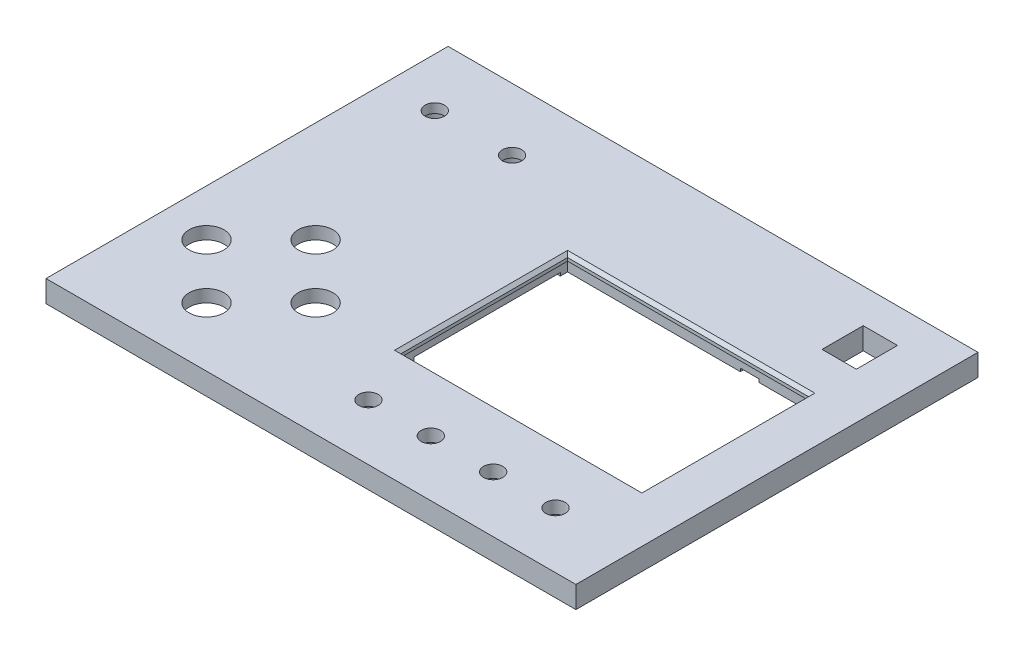
SolidWorks part; units mm, degrees
ref_plane "Front Plane" through (0, 0, 0) normal (0, 0, 1) x (1, 0, 0)
ref_plane "Top Plane" through (0, 0, 0) normal (0, 1, 0) x (1, 0, 0)
ref_plane "Right Plane" through (0, 0, 0) normal (1, 0, 0) x (0, 0, -1)
sketch "Sketch1" plane through (0, 0, 0) normal (0, 1, 0) x (1, 0, 0)
  line L1 (52.5, -34.5) -> (-52.5, -34.5)
  line L2 (52.5, -34.5) -> (52.5, 34.5)
  line L3 (52.5, 34.5) -> (-52.5, 34.5)
  line L4 (-52.5, -34.5) -> (-52.5, 34.5)
  line L5 (52.5, -34.5) -> (-52.5, 34.5) construction
  line L6 (52.5, 34.5) -> (-52.5, -34.5) construction
  point P0 (0, 0)
  dimension "D1" = 105
  dimension "D2" = 69
extrude "Boss-Extrude1" add sketch "Sketch1" along normal blind 5
extrude "Cut-Extrude1" cut sketch "Sketch2" against normal through all
sketch "Sketch2" plane through (17.0721, 0, 5.1034) normal (0, -1, 0) x (-1, 0, 0)
  line L0 (59.7281, 33.0909) -> (-27.1079, 33.0909)
  line L1 (-27.1079, 33.0909) -> (-27.1079, -24.4081)
  line L2 (-27.1079, -24.4081) -> (59.7281, -24.4081)
  line L3 (59.7281, -24.4081) -> (59.7281, 33.0909)
  line L8 (-26.1079, -23.4081) -> (58.7281, -23.4081) construction
  line L9 (-26.1079, 32.0909) -> (-26.1079, -23.4081) construction
  line L10 (58.7281, 32.0909) -> (-26.1079, 32.0909) construction
  line L11 (58.7281, -23.4081) -> (58.7281, 32.0909) construction
extrude "Cut-Extrude2" cut sketch "Sketch3" against normal blind 1
sketch "Sketch3" plane through (17.0721, 0, 5.1034) normal (0, -1, 0) x (-1, 0, 0)
  line L1 (59.8221, 30.7659) -> (54.5248, 30.7659)
  line L2 (59.8221, 30.7659) -> (59.8221, -16.2341) construction
  line L3 (59.8221, -16.2341) -> (54.5248, -16.2341)
  line L8 (65.3221, 30.2659) -> (60.3221, 30.2659) construction
  line L9 (60.3221, 30.2659) -> (60.3221, -15.7341) construction
  line L10 (60.3221, -15.7341) -> (65.3221, -15.7341) construction
  line L11 (65.3221, -15.7341) -> (65.3221, 30.2659) construction
  line L12 (54.5248, 30.7659) -> (54.5248, -16.2341)
  line L20 (65.8221, 30.7659) -> (59.8221, 30.7659)
  line L21 (59.8221, 30.7659) -> (59.8221, -16.2341) construction
  line L22 (59.8221, -16.2341) -> (65.8221, -16.2341)
  line L23 (65.8221, -16.2341) -> (65.8221, 30.7659)
extrude "Cut-Extrude3" cut sketch "Sketch4" against normal blind 1
sketch "Sketch4" plane through (17.0721, 0, 5.1034) normal (0, -1, 0) x (-1, 0, 0)
  line L8 (69.5721, -29.3966) -> (69.5721, 69.6034)
  line L10 (-35.4279, 69.6034) -> (-35.4279, -29.3966)
  line L11 (-35.4279, -29.3966) -> (69.5721, -29.3966)
  line L16 (3.8121, 35.2559) -> (-1.1879, 35.2559)
  line L17 (-1.1879, 35.2559) -> (-1.1879, 32.7559)
  line L18 (-1.1879, 32.7559) -> (3.8121, 32.7559)
  line L19 (3.8121, 32.7559) -> (3.8121, 35.2559)
  line L20 (69.5721, 69.6034) -> (-35.4279, 69.6034)
  line L28 (4.3121, 35.7559) -> (-1.6879, 35.7559)
  line L29 (-1.6879, 35.7559) -> (-1.6879, 32.2559)
  line L30 (-1.6879, 32.2559) -> (4.3121, 32.2559)
  line L31 (4.3121, 32.2559) -> (4.3121, 35.7559)
extrude "Cut-Extrude4" cut sketch "Sketch5" against normal through all contours L3 L2 A3 L5 A2 L4 | L2 L3 L4 A4 L6 A5
sketch "Sketch5" plane through (17.0721, 0, 5.1034) normal (0, -1, 0) x (-1, 0, 0)
  line L2 (-27.1779, 33.1034) -> (-27.1779, 13.8376)
  line L3 (-27.1779, 5.1034) -> (-31.6779, 5.1034) construction
  line L4 (-31.6779, -0.8966) -> (-31.6779, 11.1034)
  line L5 (-30.1159, 12.6653) -> (-28.3501, 12.6653)
  line L6 (-29.4785, -3.0961) -> (-28.6478, -3.0961)
  line L7 (-27.1779, 5.1034) -> (-27.1779, 13.8376) construction
  line L8 (-27.1779, -4.566) -> (-18.8659, -4.566)
  line L9 (-27.1779, -4.566) -> (-27.1779, 5.1034)
  line L10 (-27.1779, 13.8376) -> (-18.8659, 13.8376)
  line L11 (-18.8659, -4.566) -> (-18.8659, 13.8376)
  line L12 (-27.1779, 13.8376) -> (-27.1779, 5.1034) construction
  line L13 (-27.1779, 5.1034) -> (-27.1779, -22.8966)
  arc A2 (-31.6779, 11.1034) -> (-30.1159, 12.6653) centre (-30.1159, 11.1034) cw
  arc A3 (-28.3501, 12.6653) -> (-27.1779, 13.8376) centre (-28.3501, 13.8376) ccw
  arc A4 (-31.6779, -0.8966) -> (-29.4785, -3.0961) centre (-29.4785, -0.8966) ccw
  arc A5 (-28.6478, -3.0961) -> (-27.1779, -4.566) centre (-28.6478, -4.566) cw
  point P8 (-31.6779, 5.1034)
extrude "Cut-Extrude7" cut sketch "Sketch9" against normal blind 4
sketch "Sketch9" plane through (17.0721, 0, 5.1034) normal (0, -1, 0) x (-1, 0, 0)
  circle A4 centre (-28.6779, -22.8966) radius 1.5 construction
  circle A5 centre (62.8221, -22.8966) radius 1.5 construction
  circle A6 centre (62.8221, 33.1034) radius 1.5 construction
  circle A7 centre (-28.6779, 33.1034) radius 1.5 construction
  circle A8 centre (-28.6779, 33.1034) radius 1
  circle A9 centre (62.8221, 33.1034) radius 1
  circle A10 centre (-28.6779, -22.8966) radius 1
  circle A11 centre (62.8221, -22.8966) radius 1
sketch "Sketch7" plane through (0, 5, 0) normal (0, 1, 0) x (1, 0, 0)
  line L1 (52.5, 34.5) -> (-52.5, 34.5)
  line L2 (52.5, 34.5) -> (52.5, 64.5)
  line L3 (52.5, 64.5) -> (-52.5, 64.5)
  line L4 (-52.5, 34.5) -> (-52.5, 64.5)
  line L5 (-52.5, -34.5) -> (52.5, -34.5)
  line L6 (-52.5, -34.5) -> (-52.5, -64.5)
  line L7 (-52.5, -64.5) -> (52.5, -64.5)
  line L8 (52.5, -34.5) -> (52.5, -64.5)
  line M17 (-52.5, -34.5) -> (52.5, -34.5)
  dimension "D1" = 30
  dimension "D2" = 30
extrude "Boss-Extrude2" add sketch "Sketch7" against normal up to surface (5 mm away) contours L8 L5 L7 M17 | L1 L4 L3 L2 up to face at (-45.75, 0, -29)
sketch "Sketch8" plane through (0, 5, 0) normal (0, 1, 0) x (1, 0, 0)
  line L0 (52.5, 29.2726) -> (52.5, 64.5) construction
  line L1 (52.5, -64.5) -> (52.5, 64.5) construction
  line L2 (52.5, 46.8863) -> (26.68, 46.8863) construction
  line L3 (-52.5, 64.5) -> (-52.5, -64.5) construction
  line L4 (19.635, 46.8863) -> (19.635, 53.4863) construction
  line L5 (37.68, 40.2863) -> (26.68, 40.2863)
  line L6 (37.68, 40.2863) -> (37.68, 53.4863)
  line L7 (37.68, 53.4863) -> (26.68, 53.4863)
  line L8 (26.68, 40.2863) -> (26.68, 53.4863)
  line L9 (37.68, 40.2863) -> (26.68, 53.4863) construction
  line L10 (37.68, 53.4863) -> (26.68, 40.2863) construction
  line L11 (19.635, 40.2863) -> (8.635, 40.2863) construction
  line L12 (8.635, 40.2863) -> (8.635, 46.8863) construction
  line L13 (19.635, 53.4863) -> (8.635, 53.4863) construction
  line L14 (1.59, 46.8863) -> (1.59, 53.4863) construction
  line L15 (1.59, 40.2863) -> (-9.41, 40.2863) construction
  line L16 (-9.41, 46.8863) -> (-9.41, 53.4863) construction
  line L17 (1.59, 53.4863) -> (-9.41, 53.4863) construction
  line L18 (-16.455, 40.2863) -> (-16.455, 46.8863) construction
  line L19 (-16.455, 40.2863) -> (-27.455, 40.2863) construction
  line L20 (-27.455, 40.2863) -> (-27.455, 46.8863) construction
  line L21 (-16.455, 53.4863) -> (-27.455, 53.4863) construction
  line L22 (-34.5, 40.2863) -> (-34.5, 46.8863) construction
  line L23 (-34.5, 40.2863) -> (-45.5, 40.2863) construction
  line L24 (-45.5, 40.2863) -> (-45.5, 46.8863) construction
  line L25 (-34.5, 53.4863) -> (-45.5, 53.4863) construction
  line L26 (-45.5, 46.8863) -> (-45.5, 53.4863) construction
  line L27 (-34.5, 46.8863) -> (-34.5, 53.4863) construction
  line L28 (-27.455, 46.8863) -> (-34.5, 46.8863) construction
  line L29 (-34.5, 46.8863) -> (-52.5, 46.8863) construction
  line L30 (-16.455, 46.8863) -> (-27.455, 46.8863) construction
  line L31 (-27.455, 46.8863) -> (-27.455, 53.4863) construction
  line L32 (-16.455, 46.8863) -> (-16.455, 53.4863) construction
  line L33 (1.59, 40.2863) -> (1.59, 46.8863) construction
  line L34 (-9.41, 40.2863) -> (-9.41, 46.8863) construction
  line L35 (-9.41, 46.8863) -> (-16.455, 46.8863) construction
  line L36 (8.635, 46.8863) -> (8.635, 53.4863) construction
  line L37 (8.635, 46.8863) -> (1.59, 46.8863) construction
  line L38 (1.59, 46.8863) -> (-9.41, 46.8863) construction
  line L39 (19.635, 40.2863) -> (19.635, 46.8863) construction
  line L40 (26.68, 46.8863) -> (19.635, 46.8863) construction
  line L41 (19.635, 46.8863) -> (8.635, 46.8863) construction
  point P9 (32.18, 46.8863)
  point P14 (-40, 53.4863)
  dimension "D1" = 13.2
  dimension "D2" = 11
  dimension "D3" = 20.32
  dimension "D5" = 12.5
  dimension "D6" = 11
  dimension "D4" = 5
extrude "Cut-Extrude6" cut sketch "Sketch8" against normal through all
sketch "Sketch10" plane through (0, 5, 0) normal (0, 1, 0) x (1, 0, 0)
  line L0 (44.18, 27.9875) -> (44.18, 8.7342) construction
  line L1 (-52.5, 64.5) -> (52.5, 64.5)
  line L2 (-52.5, 64.5) -> (-52.5, -34.5)
  line L3 (-52.5, -34.5) -> (52.5, -34.5) construction
  line L4 (52.5, 64.5) -> (52.5, -34.5)
  line L5 (44.18, -9.6693) -> (44.18, -29.5115) construction
  line L6 (44.18, -29.5115) -> (-42.656, -29.5115) construction
  line L7 (-42.656, -29.5115) -> (-42.656, 27.9875) construction
  line L8 (-42.656, 27.9875) -> (44.18, 27.9875) construction
  line L9 (37.68, 40.2863) -> (37.68, 53.4863) construction
  line L10 (26.68, 40.2863) -> (37.68, 40.2863) construction
  line L11 (37.68, 53.4863) -> (26.68, 53.4863) construction
  line L12 (26.68, 53.4863) -> (26.68, 40.2863) construction
  line L29 (44.18, 27.9875) -> (44.18, 8.7342)
  line L30 (44.18, -9.6693) -> (44.18, -29.5115)
  line L31 (44.18, -29.5115) -> (-42.656, -29.5115)
  line L32 (-42.656, -29.5115) -> (-42.656, 27.9875)
  line L33 (-42.656, 27.9875) -> (44.18, 27.9875)
  line L34 (37.68, 40.2863) -> (37.68, 53.4863)
  line L35 (26.68, 40.2863) -> (37.68, 40.2863)
  line L36 (37.68, 53.4863) -> (26.68, 53.4863)
  line L37 (26.68, 53.4863) -> (26.68, 40.2863)
  line L54 (44.18, -9.6693) -> (44.18, 8.7342)
  line L59 (-52.5, 64.5) -> (-52.5, -64.5)
  line L60 (-52.5, -64.5) -> (52.5, -64.5)
  line L61 (52.5, -64.5) -> (52.5, 64.5)
  line L62 (52.5, 64.5) -> (-52.5, 64.5)
  line L63 (-52.5, 64.5) -> (-52.5, -64.5)
  line L64 (-52.5, -64.5) -> (52.5, -64.5)
  line L65 (52.5, -64.5) -> (52.5, 64.5)
  line L66 (52.5, 64.5) -> (-52.5, 64.5)
  dimension "D1" = 0
extrude "Boss-Extrude3" add sketch "Sketch10" along normal blind 2
sketch "Sketch11" plane through (0, 7, 0) normal (0, 1, 0) x (1, 0, 0)
  line L4 (-42.656, 27.9875) -> (-42.656, -29.5115)
  line L5 (44.18, 27.9875) -> (-42.656, 27.9875)
  line L6 (-42.656, -29.5115) -> (44.18, -29.5115)
  line L7 (44.18, -29.5115) -> (44.18, 27.9875)
  line L8 (36.68, -29.5115) -> (36.68, -27.5115) construction
  line L9 (44.18, -29.5115) -> (36.68, -29.5115)
  line L10 (44.18, -29.5115) -> (44.18, 27.9875)
  line L11 (44.18, 27.9875) -> (36.68, 27.9875)
  line L12 (36.68, -27.5115) -> (36.68, 25.9875)
  line L13 (-42.656, -29.5115) -> (36.68, -29.5115)
  line L14 (-42.656, -29.5115) -> (-42.656, -27.5115)
  line L15 (-40.656, -27.5115) -> (36.68, -27.5115)
  line L16 (36.68, -29.5115) -> (36.68, -27.5115) construction
  line L17 (-42.656, 27.9875) -> (36.68, 27.9875)
  line L18 (-42.656, 27.9875) -> (-42.656, 25.9875)
  line L19 (-40.656, 25.9875) -> (36.68, 25.9875)
  line L20 (36.68, 27.9875) -> (36.68, 25.9875) construction
  line L21 (-42.656, 27.9875) -> (-40.656, 27.9875)
  line L22 (-42.656, 27.9875) -> (-42.656, -29.5115)
  line L23 (-42.656, -29.5115) -> (-40.656, -29.5115)
  line L24 (-40.656, 25.9875) -> (-40.656, -27.5115)
  line L25 (-40.656, -27.5115) -> (-40.656, -29.5115) construction
  line L26 (-42.656, -27.5115) -> (-40.656, -27.5115) construction
  line L27 (-42.656, 25.9875) -> (-40.656, 25.9875) construction
  line L28 (-40.656, 27.9875) -> (-40.656, 25.9875) construction
  line L29 (36.68, 25.9875) -> (36.68, 27.9875) construction
  dimension "D1" = 7.5
  dimension "D2" = 2
  dimension "D3" = 2
  dimension "D4" = 2
extrude "Boss-Extrude4" add sketch "Sketch11" against normal blind 2
chamfer "Chamfer1" distance 1 angle 45 4 edges at (-1.988, 7, -25.9875) (-40.656, 7, 0.762) (-1.988, 7, 27.5115) (36.68, 7, 0.762)
sketch "Sketch12" plane through (0, 7, 0) normal (0, 1, 0) x (1, 0, 0)
  line L0 (-52.5, -64.5) -> (52.5, -64.5) construction
  line L1 (-52.5, -64.5) -> (-117.5, -64.5)
  line L2 (-52.5, -64.5) -> (-52.5, 64.5)
  line L3 (-52.5, 64.5) -> (-117.5, 64.5)
  line L4 (-117.5, -64.5) -> (-117.5, 64.5)
  line L5 (52.5, -64.5) -> (117.5, -64.5)
  line L6 (52.5, -64.5) -> (52.5, 64.5)
  line L7 (52.5, 64.5) -> (117.5, 64.5)
  line L8 (117.5, -64.5) -> (117.5, 64.5)
  line L9 (52.5, 64.5) -> (-52.5, 64.5) construction
  line L10 (-67.5, -28) -> (-102.5, -28) construction
  line L11 (-85, -45.5) -> (-85, -10.5) construction
  circle A0 centre (-85, -10.5) radius 5.6
  circle A1 centre (-85, -45.5) radius 5.6
  circle A2 centre (-102.5, -28) radius 5.6
  circle A3 centre (-67.5, -28) radius 5.6
  circle A4 centre (-85, -10.5) radius 8.5 construction
  circle A5 centre (-102.5, -28) radius 8.5 construction
  circle A6 centre (-67.5, -28) radius 8.5 construction
  circle A7 centre (-85, -45.5) radius 8.5 construction
  point P4 (-85, 64.5)
  point P19 (-85, -28)
  line M72 (-52.5, 64.5) -> (-52.5, -64.5)
  dimension "D3" = 11.2
  dimension "D7" = 17
  dimension "D8" = 17
  dimension "D1" = 65
  dimension "D2" = 65
  dimension "D4" = 35
  dimension "D5" = 75
  dimension "D6" = 35
extrude "Boss-Extrude5" add sketch "Sketch12" against normal up to surface (7 mm away) contours L4 L1 L3 M72
sketch "Sketch15" plane through (0, 7, 0) normal (0, 1, 0) x (1, 0, 0)
  line L0 (-117.5, -64.5) -> (52.5, -64.5) construction
  line L1 (-41.656, -28.5115) -> (37.68, -28.5115)
  line L2 (-41.656, -28.5115) -> (-41.656, -64.5)
  line L3 (-41.656, -64.5) -> (37.68, -64.5)
  line L4 (37.68, -28.5115) -> (37.68, -64.5)
  line L5 (-41.656, -46.5057) -> (37.68, -46.5057) construction
  circle A0 centre (-32.041, -46.5057) radius 3.1
  circle A1 centre (-12.041, -46.5057) radius 3.1
  circle A2 centre (7.959, -46.5057) radius 3.1
  circle A3 centre (27.959, -46.5057) radius 3.1
  dimension "D1" = 6.2
  dimension "D2" = 9.615
  dimension "D3" = 4
extrude "Cut-Extrude8" cut sketch "Sketch15" against normal through all contours A0 L5 | A1 L5 | L5 A1 | L5 A0 | A2 L5 | L5 A2 | A3 L5 | L5 A3
sketch "Sketch16" plane through (0, 0, 0) normal (0, -1, 0) x (1, 0, 0)
  circle A0 centre (27.959, 46.5057) radius 3.1 construction
  circle A1 centre (7.959, 46.5057) radius 3.1 construction
  circle A2 centre (-12.041, 46.5057) radius 3.1 construction
  circle A3 centre (-32.041, 46.5057) radius 3.1 construction
  circle A4 centre (27.959, 46.5057) radius 3.1
  circle A5 centre (7.959, 46.5057) radius 3.1
  circle A6 centre (-12.041, 46.5057) radius 3.1
  circle A7 centre (-32.041, 46.5057) radius 3.1
  circle A8 centre (-32.041, 46.5057) radius 5.5
  circle A9 centre (-12.041, 46.5057) radius 5.5
  circle A10 centre (7.959, 46.5057) radius 5.5
  circle A11 centre (27.959, 46.5057) radius 5.5
  dimension "D1" = 11
extrude "Cut-Extrude9" cut sketch "Sketch16" against normal blind 3
sketch "Sketch18" plane through (0, 0, 0) normal (0, -1, 0) x (1, 0, 0)
  circle A0 centre (-85, 45.5) radius 10
  circle A1 centre (-102.5, 28) radius 10
  circle A2 centre (-85, 10.5) radius 10
  circle A3 centre (-67.5, 28) radius 10
  dimension "D1" = 20
extrude "Cut-Extrude10" cut sketch "Sketch18" against normal blind 3
chamfer "Chamfer2" distance 1 angle 45 4 edges at (-85, 0, 0.5) (-67.5, 0, 18) (-102.5, 0, 18) (-85, 0, 35.5)
sketch "Sketch19" plane through (0, 0, 0) normal (0, -1, 0) x (1, 0, 0)
  line L0 (-117.5, -64.5) -> (52.5, -64.5) construction
  line L1 (-42.656, -27.9875) -> (26.68, -27.9875)
  line L2 (-42.656, -27.9875) -> (-42.656, -64.5)
  line L4 (26.68, -27.9875) -> (26.68, -64.5)
  line L5 (26.68, -64.5) -> (-7.988, -64.5) construction
  line L6 (26.68, -64.5) -> (-7.988, -64.5) construction
  line L7 (18.196, -64.5) -> (0.496, -64.5)
  line L8 (18.196, -64.5) -> (18.196, -51)
  line L9 (18.196, -51) -> (0.496, -51)
  line L10 (0.496, -64.5) -> (0.496, -51)
  point P12 (9.346, -64.5)
  point P13 (9.346, -64.5)
  line M50 (-117.5, -64.5) -> (52.5, -64.5)
  dimension "D1" = 17.7
  dimension "D2" = 13.5
extrude "Cut-Extrude11" cut sketch "Sketch19" against normal blind 2 contours L10 L8 L9 M50
sketch "Sketch20" plane through (0, 2, 0) normal (0, -1, 0) x (1, 0, 0)
  line L0 (5.496, -62.5) -> (10.696, -62.5) construction
  line L1 (5.496, -61.0866) -> (10.696, -61.0866)
  line L3 (18.196, -64.5) -> (18.196, -51) construction
  line L4 (0.496, -64.5) -> (0.496, -51) construction
  line L5 (0.496, -64.5) -> (18.196, -64.5) construction
  line L6 (18.196, -64.5) -> (18.196, -51) construction
  line L7 (0.496, -64.5) -> (18.196, -64.5)
  line L8 (0.496, -64.5) -> (0.496, -61.0866)
  line L9 (0.496, -61.0866) -> (18.196, -61.0866)
  line L10 (18.196, -64.5) -> (18.196, -61.0866)
  line L12 (0.496, -51) -> (18.196, -51)
  line L13 (0.496, -51) -> (0.496, -55.2225)
  line L14 (0.496, -55.2225) -> (18.196, -55.2225)
  line L15 (18.196, -51) -> (18.196, -55.2225)
  point P2 (8.096, -62.5)
  dimension "D1" = 7.5
  dimension "D2" = 5
  dimension "D3" = 2
extrude "Cut-Extrude12" cut sketch "Sketch20" against normal blind 1
sketch "Sketch22" plane through (0, 0, 0) normal (0, -1, 0) x (1, 0, 0)
  line L0 (-117.5, -64.5) -> (0.496, -64.5) construction
  line L1 (-24.8391, -64.5) -> (-60.3391, -64.5)
  line L2 (-24.8391, -64.5) -> (-24.8391, -54.5)
  line L3 (-24.8391, -54.5) -> (-60.3391, -54.5)
  line L4 (-60.3391, -64.5) -> (-60.3391, -54.5)
  circle A0 centre (-57.8391, -59.5) radius 1
  dimension "D4" = 2
  dimension "D1" = 10
  dimension "D2" = 35.5
  dimension "D3" = 2.5
extrude "Cut-Extrude13" cut sketch "Sketch22" against normal blind 2
sketch "Sketch23" plane through (0, 0, 0) normal (0, -1, 0) x (1, 0, 0)
  circle A1 centre (-57.8391, -59.5) radius 1
  circle A2 centre (-57.8391, -59.5) radius 1
  dimension "D1" = 0
extrude "Cut-Extrude14" cut sketch "Sketch23" against normal blind 4
sketch "Sketch24" plane through (0, 2, 0) normal (0, -1, 0) x (1, 0, 0)
  line L0 (-35.8391, -63) -> (-25.8391, -63) construction
  line L1 (-35.8391, -62.0036) -> (-25.8391, -62.0036)
  line L2 (-35.8391, -63.9964) -> (-25.8391, -63.9964)
  line L3 (-60.3391, -64.5) -> (-24.8391, -64.5) construction
  line L4 (-24.8391, -64.5) -> (-24.8391, -54.5) construction
  arc A0 (-35.8391, -62.0036) -> (-35.8391, -63.9964) centre (-35.8391, -63) ccw
  arc A1 (-25.8391, -63.9964) -> (-25.8391, -62.0036) centre (-25.8391, -63) ccw
  point P2 (-30.8391, -63)
  dimension "D1" = 1.5
  dimension "D2" = 6
  dimension "D3" = 10
extrude "Cut-Extrude15" cut sketch "Sketch24" against normal blind 1
sketch "Sketch25" plane through (0, 7, 0) normal (0, 1, 0) x (1, 0, 0)
  line L0 (52.5, 64.5) -> (-117.5, 64.5) construction
  circle A0 centre (-101.7793, 44.5) radius 3.1
  circle A1 centre (-76.9864, 44.5) radius 3.1
  dimension "D1" = 6.2
  dimension "D2" = 20
extrude "Cut-Extrude16" cut sketch "Sketch25" against normal through all
sketch "Sketch26" plane through (0, 0, 0) normal (0, -1, 0) x (1, 0, 0)
  circle A0 centre (-101.7793, -44.5) radius 5.15
  circle A1 centre (-76.9864, -44.5) radius 5.15
  dimension "D1" = 10.3
extrude "Cut-Extrude17" cut sketch "Sketch26" against normal blind 4
